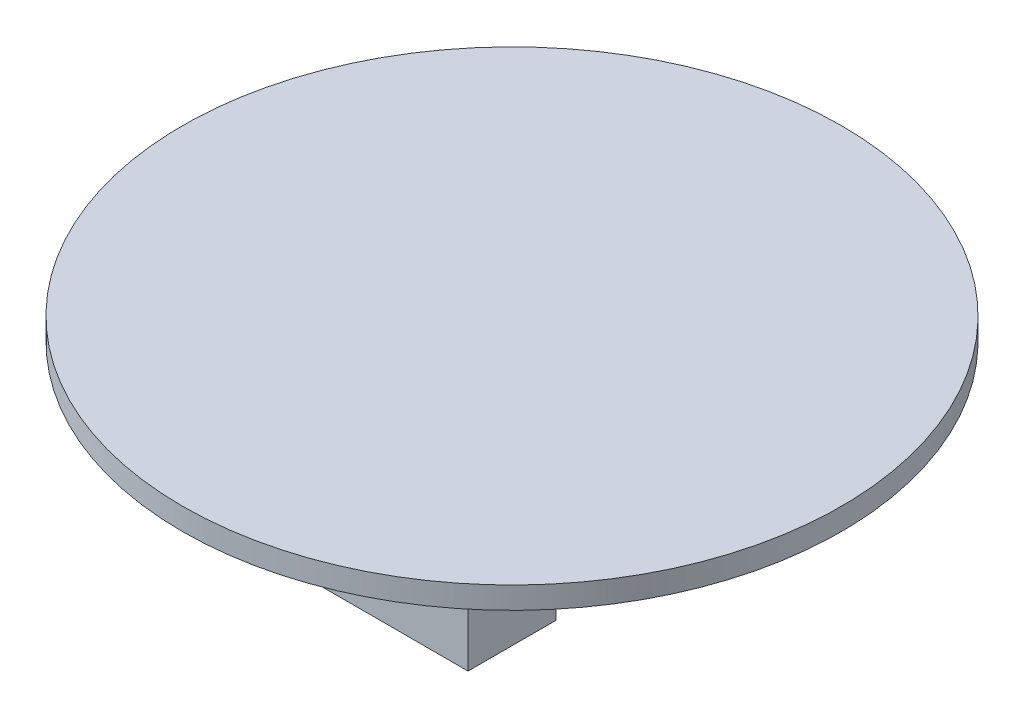
SolidWorks part; units mm, degrees
ref_plane "Front Plane" through (0, 0, 0) normal (0, 0, 1) x (1, 0, 0)
ref_plane "Top Plane" through (0, 0, 0) normal (0, 1, 0) x (1, 0, 0)
ref_plane "Right Plane" through (0, 0, 0) normal (1, 0, 0) x (0, 0, -1)
sketch "Sketch1" plane through (0, 0, 0) normal (0, 1, 0) x (1, 0, 0)
  circle A0 centre (0, 0) radius 75
  dimension "D1" = 150
extrude "Boss-Extrude1" add sketch "Sketch1" along normal blind 5
sketch "Sketch2" plane through (0, 0, 0) normal (0, -1, 0) x (-1, 0, 0)
  line L1 (10, -50) -> (-40, -50)
  line L2 (10, -50) -> (10, -30)
  line L3 (10, -30) -> (-40, -30)
  line L4 (-40, -50) -> (-40, -30)
  dimension "D1" = 50
  dimension "D2" = 20
  dimension "D3" = 30
  dimension "D4" = 10
extrude "Boss-Extrude2" add sketch "Sketch2" along normal blind 20
sketch "Sketch3" plane through (-10, 0, 0) normal (-1, 0, 0) x (0, 0, 1)
  line L0 (40, -26.3209) -> (40, 19.8974) construction
  line L1 (50, -20) -> (50, 0) construction
  line L2 (30, -20) -> (30, 0) construction
  line L3 (32, -15) -> (32, -20)
  line L4 (50, -20) -> (30, -20) construction
  line L5 (48, -15) -> (48, -20)
  line L6 (32, -20) -> (48, -20)
  arc A0 (48, -15) -> (32, -15) centre (40, -15) ccw
  dimension "D1" = 8
  dimension "D2" = 5
extrude "Cut-Extrude1" cut sketch "Sketch3" against normal blind 18 from offset 2.5 offset against normal yes
sketch "Sketch4" plane through (10.5, 0, 0) normal (-1, 0, 0) x (0, 0, 1)
  line L0 (31, -15) -> (31, -20)
  line L1 (50, -20) -> (30, -20) construction
  line L2 (40, 8.3565) -> (40, -32.2568) construction
  line L3 (49, -15) -> (49, -20)
  line L4 (31, -20) -> (49, -20)
  arc A0 (49, -15) -> (31, -15) centre (40, -15) ccw
  dimension "D1" = 9
extrude "Cut-Extrude2" cut sketch "Sketch4" against normal blind 27
sketch "Sketch5" plane through (-7.5, 0, 0) normal (1, 0, 0) x (0, 0, -1)
  line L0 (-36.25, -15) -> (-36.25, -20)
  line L1 (-32, -20) -> (-48, -20) construction
  line L2 (-43.75, -15) -> (-43.75, -20)
  line L3 (-36.25, -20) -> (-43.75, -20)
  arc A0 (-36.25, -15) -> (-43.75, -15) centre (-40, -15) ccw
  arc A1 (-32, -15) -> (-48, -15) centre (-40, -15) ccw construction
  dimension "D1" = 3.75
extrude "Cut-Extrude3" cut sketch "Sketch5" against normal up to next
sketch "Sketch6" plane through (-10, 0, 0) normal (-1, 0, 0) x (0, 0, 1)
  line L0 (40, -29.8539) -> (40, 13.9436) construction
  line L1 (50, -20) -> (50, 0) construction
  line L2 (30, -20) -> (30, 0) construction
  circle A0 centre (45.5, -15) radius 1
  circle A1 centre (34.5, -15) radius 1
  dimension "D2" = 2
  dimension "D1" = 11
extrude "Cut-Extrude4" cut sketch "Sketch6" against normal up to next
